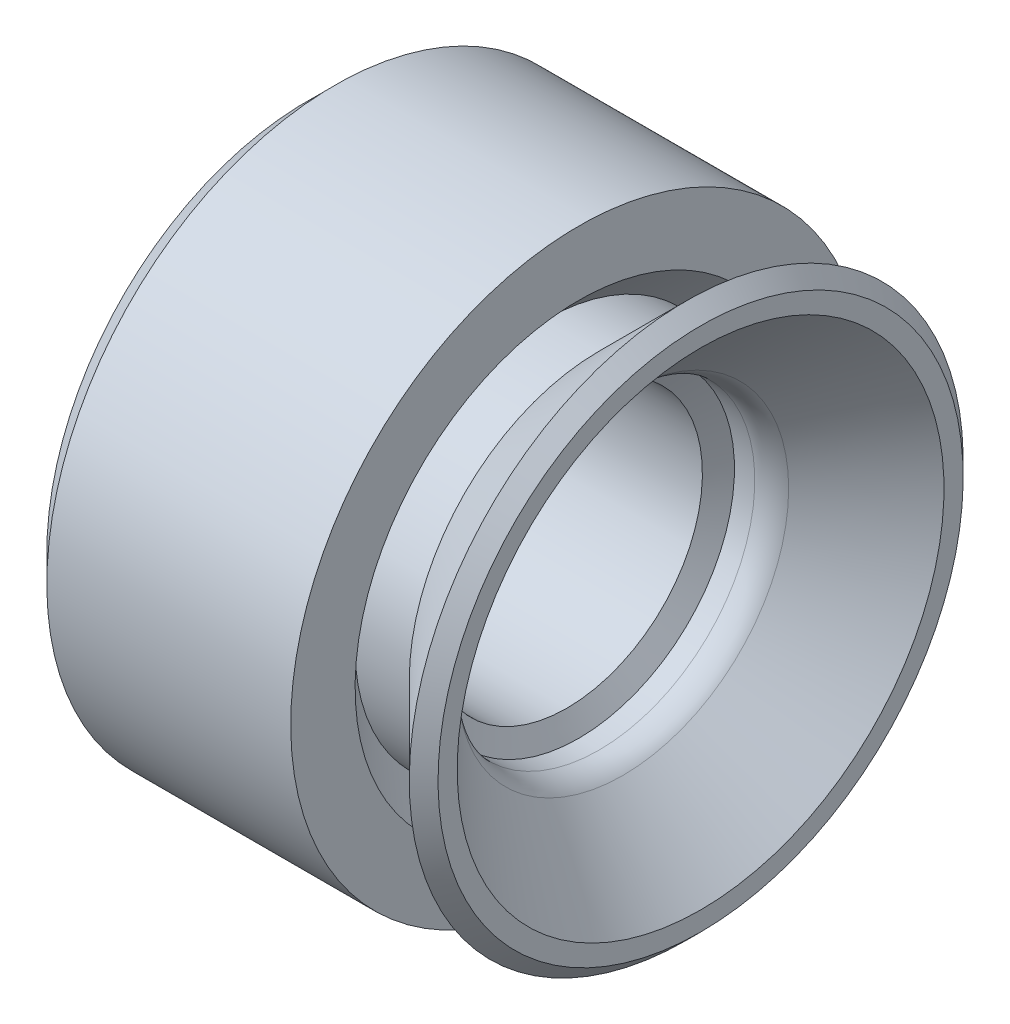
SolidWorks part; units mm, degrees
ref_plane "Спереди" through (0, 0, 0) normal (0, 0, 1) x (1, 0, 0)
ref_plane "Сверху" through (0, 0, 0) normal (0, 1, 0) x (1, 0, 0)
ref_plane "Справа" through (0, 0, 0) normal (1, 0, 0) x (0, 0, -1)
sketch "Эскиз22" plane through (0, 0, 0) normal (0, 0, 1) x (1, 0, 0)
  line L0 (0, 0) -> (2, 0) construction
  line L1 (0, 0) -> (0, -2.8) construction
  line L2 (2, 0) -> (2, -4.3) construction
  line L3 (0, -2.8) -> (0.5, -2.8) construction
  line L4 (2, -4.3) -> (0.5, -2.8) construction
  line L5 (0.5, -2.8) -> (-0.3, -2.8)
  line L6 (0.5, -2.8) -> (1.7879, -4.0879)
  line L7 (0.2, -2.3) -> (0.5, -2.3)
  line L8 (0.8536, -2.4464) -> (2, -3.5929)
  line L9 (1.7879, -4.0879) -> (2, -3.8757)
  line L10 (2, -3.5929) -> (2, -3.8757)
  line L11 (0.2, -3.3) -> (0.2, -4.25)
  line L12 (0.2, -3.3) -> (0.2, -2.3) construction
  line L13 (0.2, -2.3) -> (0.0268, -2)
  line L14 (0.0268, -2) -> (-3.5113, -2)
  line L15 (0.2, -4.25) -> (-3.4, -4.25)
  line L16 (-3.8, -3.85) -> (-3.8, -2.5)
  line L17 (-3.4, -4.25) -> (-3.8, -3.85)
  line L18 (-0.3804, -2.5) -> (-3.8, -2.5) construction
  line L19 (-3.8, -2.5) -> (-3.5113, -2)
  line L20 (0.2, -3.3) -> (-0.3, -2.8)
  arc A0 (0.8536, -2.4464) -> (0.5, -2.3) centre (0.5, -2.8) ccw
  point P5 (-3.8, -4.25)
  point P13 (2.1414, -3.7343)
  dimension "D7" = 0.2
  dimension "D1" = 2
  dimension "D2" = 45
  dimension "D3" = 8.6
  dimension "D4" = 0.5
  dimension "D5" = 5.6
  dimension "D6" = 0.5
  dimension "D9" = 60
  dimension "D10" = 4
  dimension "D11" = 8.5
  dimension "D12" = 4
  dimension "D13" = 5
  dimension "D14" = 120
  dimension "D15" = 45
  dimension "D17" = 0.5
  dimension "D8" = 0.2
revolve "Основание-Повернуть" add sketch "Эскиз22" angle 360 about L0
cosmetic thread "Условное изображение резьбы1" parameters "D2"=4
sketch "Эскиз23" plane through (0.2, 0, 0) normal (1, 0, 0) x (0, 0, -1)
  line L0 (0, 0) -> (7.5, 0) construction
  line L1 (0, 0) -> (7.4518, 0.849) construction
  line L2 (2.782, 0.317) -> (7.4518, 0.849)
  line L3 (2.8, 0) -> (7.5, 0)
  arc A0 (7.5, 0) -> (7.4518, 0.849) centre (0, 0) ccw
  circle A2 centre (0, 0) radius 2.8 construction
  arc A3 (2.8, 0) -> (2.782, 0.317) centre (0, 0) ccw
  dimension "D2" = 7.5
  dimension "D1" = 6.5
extrude "Вырез-Вытянуть4" [suppressed] cut sketch "Эскиз23" against normal blind 0.2 draft 45
pattern_circular "Круговой массив2" [suppressed] count 48 every 8
